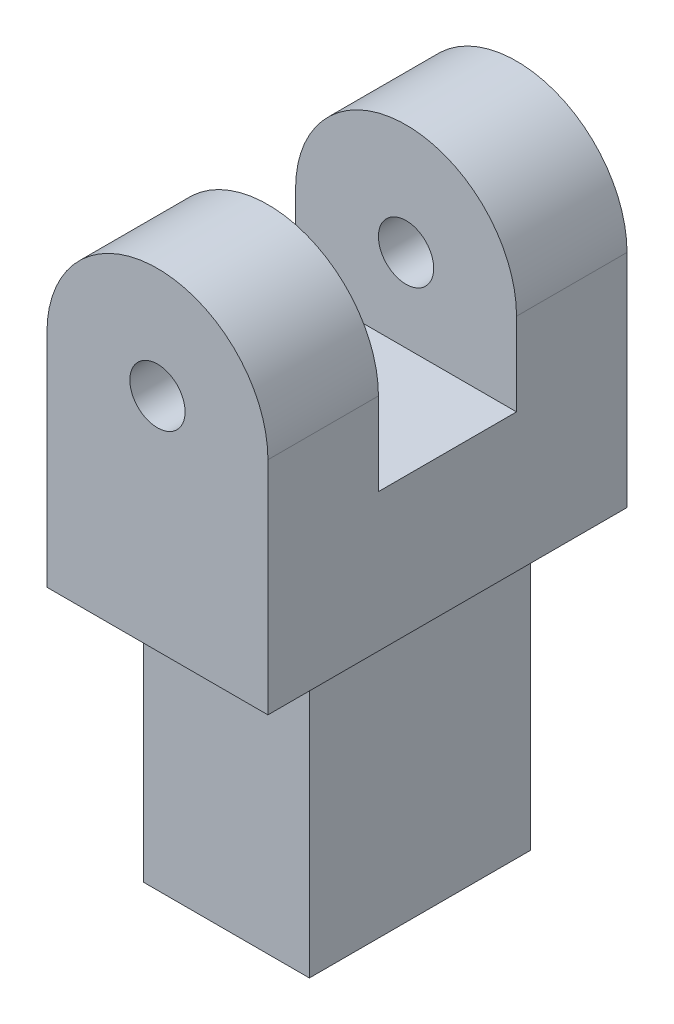
SolidWorks part; units mm, degrees
ref_plane "Front Plane" through (0, 0, 0) normal (0, 0, 1) x (1, 0, 0)
ref_plane "Top Plane" through (0, 0, 0) normal (0, 1, 0) x (1, 0, 0)
ref_plane "Right Plane" through (0, 0, 0) normal (1, 0, 0) x (0, 0, -1)
sketch "Sketch1" plane through (0, 0, 0) normal (0, 1, 0) x (1, 0, 0)
  line L0 (-4, -6.5) -> (4, -6.5)
  line L1 (-4, -6.5) -> (-4, 6.5)
  line L2 (4, -6.5) -> (4, 6.5)
  line L3 (-4, 6.5) -> (4, 6.5)
  line L4 (-4, -6.5) -> (4, 6.5) construction
  line L5 (4, -6.5) -> (-4, 6.5) construction
  point P1 (0, 0)
  dimension "D1" = 13
  dimension "D2" = 8
extrude "Boss-Extrude1" add sketch "Sketch1" along normal blind 12
sketch "Sketch2" plane through (0, 12, 0) normal (0, 1, 0) x (1, 0, 0)
  line L0 (-6.5, -2.5) -> (6.5, -2.5)
  line L1 (-6.5, -2.5) -> (-6.5, 2.5)
  line L2 (6.5, -2.5) -> (6.5, 2.5)
  line L3 (-6.5, 2.5) -> (6.5, 2.5)
  line L4 (-6.5, -2.5) -> (6.5, 2.5) construction
  line L5 (6.5, -2.5) -> (-6.5, 2.5) construction
  point P1 (0, 0)
  dimension "D1" = 5
  dimension "D2" = 13
extrude "Cut-Extrude1" cut sketch "Sketch2" against normal blind 7
sketch "Sketch3" plane through (0, 0, -6.5) normal (0, 0, -1) x (-1, 0, 0)
  line L0 (-4, 12) -> (4, 12) construction
  line L1 (-4, 12) -> (-4, 0) construction
  circle A0 centre (0, 8) radius 1
  point P4 (0, 12)
  dimension "D2" = 2
  dimension "D1" = 4
  dimension "D3" = 4
extrude "Cut-Extrude2" cut sketch "Sketch3" against normal through all
sketch "Sketch4" plane through (0, 0, -6.5) normal (0, 0, -1) x (-1, 0, 0)
  line L0 (-4, 12) -> (-4, 0) construction
  line L1 (-4, 12) -> (4, 12) construction
  arc A0 (-4, 8) -> (0, 12) centre (0, 8) cw
  dimension "D1" = 4
extrude "Cut-Extrude3" cut sketch "Sketch4" against normal blind 13 and the other way through all
mirror "Mirror1" about plane through (0, 0, 0) normal (1, 0, 0) of "Cut-Extrude3"
sketch "Sketch6" plane through (0, 0, 0) normal (0, -1, 0) x (1, 0, 0)
  line L0 (-3, -4) -> (3, -4)
  line L1 (-3, -4) -> (-3, 4)
  line L2 (3, -4) -> (3, 4)
  line L3 (-3, 4) -> (3, 4)
  line L4 (-3, -4) -> (3, 4) construction
  line L5 (3, -4) -> (-3, 4) construction
  point P1 (0, 0)
  dimension "D1" = 8
  dimension "D2" = 6
extrude "Boss-Extrude3" add sketch "Sketch6" along normal blind 10
